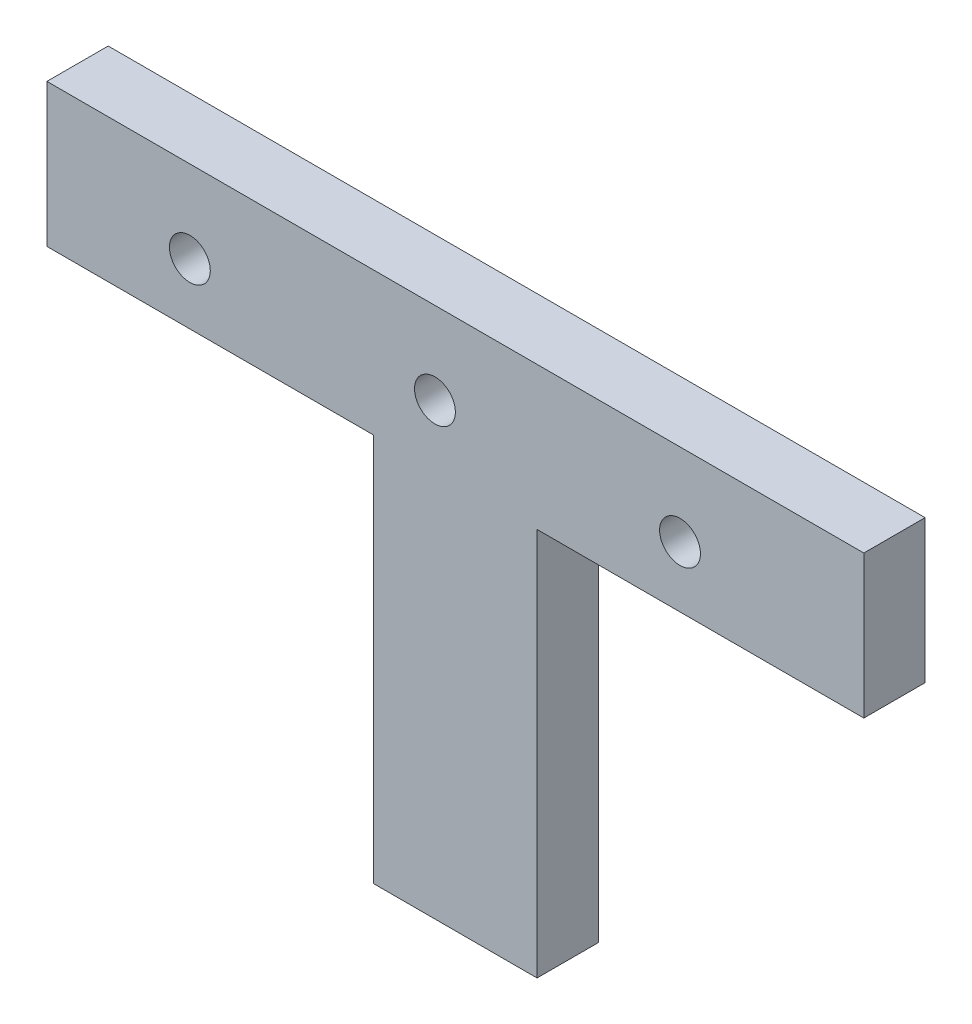
SolidWorks part; units mm, degrees
ref_plane "前基準面" through (0, 0, 0) normal (0, 0, 1) x (1, 0, 0)
ref_plane "上基準面" through (0, 0, 0) normal (0, 1, 0) x (1, 0, 0)
ref_plane "右基準面" through (0, 0, 0) normal (1, 0, 0) x (0, 0, -1)
sketch "草圖1" plane through (0, 0, 0) normal (0, 0, 1) x (1, 0, 0)
  line L0 (-40.1551, 7.2196) -> (-80.1551, 7.2196)
  line L1 (-80.1551, 7.2196) -> (-80.1551, 102.3297)
  line L2 (-80.1551, 102.3297) -> (-160.1551, 102.3297)
  line L3 (-160.1551, 102.3297) -> (-160.1551, 137.3297)
  line L4 (-160.1551, 137.3297) -> (39.8449, 137.3297)
  line L5 (39.8449, 137.3297) -> (39.8449, 102.3297)
  line L6 (39.8449, 102.3297) -> (-40.1551, 102.3297)
  line L7 (-40.1551, 102.3297) -> (-40.1551, 7.2196)
  line L8 (-60.1551, 137.3297) -> (-60.1551, 151.4898) construction
  line L9 (-60.1551, 7.2196) -> (-60.1551, -12.7977) construction
  dimension "D1" = 200
  dimension "D2" = 35
  dimension "D3" = 40
extrude "填料-伸長1" add sketch "草圖1" along normal blind 15
sketch "草圖2" plane through (0, 0, 15) normal (0, 0, 1) x (1, 0, 0)
  line L0 (39.8449, 102.3297) -> (39.8449, 137.3297) construction
  circle A0 centre (-5.1551, 117.1895) radius 5
  circle A1 centre (-65.1551, 117.1895) radius 5
  circle A2 centre (-125.1551, 117.1895) radius 5
  dimension "D1" = 10
  dimension "D2" = 10
  dimension "D3" = 10
  dimension "D4" = 60
  dimension "D5" = 60
  dimension "D6" = 45
extrude "除料-伸長1" cut sketch "草圖2" against normal through all
